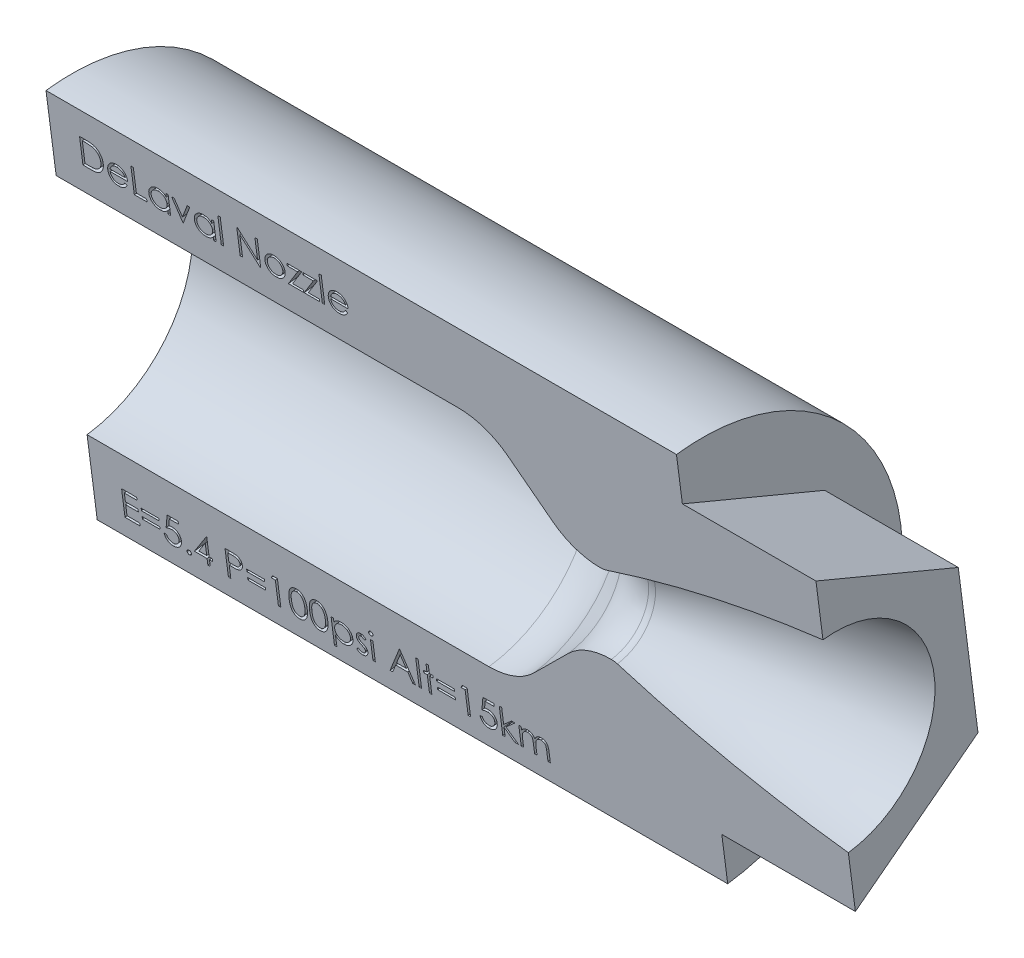
SolidWorks part; units mm, degrees
ref_plane "Front Plane" through (0, 0, 0) normal (0, 0, 1) x (1, 0, 0)
ref_plane "Top Plane" through (0, 0, 0) normal (0, 1, 0) x (1, 0, 0)
ref_plane "Right Plane" through (0, 0, 0) normal (1, 0, 0) x (0, 0, -1)
sketch "Sketch1" plane through (0, 0, 0) normal (0, 0, 1) x (1, 0, 0)
  line L0 (0, 0) -> (10.9228, 0) construction
  line L1 (0.278, 2.081) -> (10.9228, 5.9554) construction
  line L2 (-2.1553, 2.9247) -> (-4.048, 4.8174)
  line L3 (-25.4, 5.7474) -> (-25.4, 9.525)
  line L4 (-6.293, 5.7474) -> (-25.4, 5.7474)
  line L5 (-25.4, 9.525) -> (-1.7772, 9.525)
  line L6 (10.9228, 9.525) -> (10.9228, 4.7219)
  line L7 (10.9228, 4.7219) -> (12.711, 4.9733) construction
  line L8 (-1.7772, 9.525) -> (10.9228, 9.525)
  arc A0 (-2.1553, 2.9247) -> (0, 2.032) centre (0, 5.08) ccw
  arc A1 (0, 2.032) -> (0.278, 2.081) centre (0, 2.8448) ccw
  arc A2 (-4.048, 4.8174) -> (-6.293, 5.7474) centre (-6.293, 2.5724) ccw
  parabola Q0 (10.9228, 4.7219) -> (0.278, 2.081) focus (9.0524, -22.0264) apex (0.278, 2.081)
  dimension "D3" = 3.048
  dimension "D4" = 0.8128
  dimension "D11" = 3.175
  dimension "D12" = 8
  dimension "D1" = 2.032
  dimension "D2" = 10.9228
  dimension "D5" = 4.7219
  dimension "D6" = 20
  dimension "D7" = 45
  dimension "D8" = 5.7474
  dimension "D9" = 25.4
  dimension "D10" = 9.525
  dimension "D13" = 12.7
revolve "Revolve1" add sketch "Sketch1" angle 360 about L0
sketch "Sketch3" plane through (10.9228, 0, 0) normal (1, 0, 0) x (0, 0, -1)
  line L1 (0.9374, -7.2722) -> (6.7666, -2.8242)
  line L2 (6.7666, -2.8242) -> (5.8292, 4.4479)
  line L3 (5.8292, 4.4479) -> (-0.9374, 7.2722)
  line L4 (-0.9374, 7.2722) -> (-6.7666, 2.8242)
  line L5 (-6.7666, 2.8242) -> (-5.8292, -4.4479)
  line L6 (-5.8292, -4.4479) -> (0.9374, -7.2722)
  circle A0 centre (0, 0) radius 6.35 construction
  circle M7 centre (0, 0) radius 9.525
  dimension "D1" = 12.7
extrude "Cut-Extrude2" cut sketch "Sketch3" against normal blind 6.35 contours L6 L5 L4 L3 L2 L1 M7
sketch "Sketch4" plane through (10.9228, 0, 0) normal (1, 0, 0) x (0, 0, -1)
  line L0 (1.606, -12.4589) -> (-1.4282, 11.0794)
  line L1 (-1.4282, 11.0794) -> (-11.4972, 10.005)
  line L2 (-11.4972, 10.005) -> (-9.1004, -12.4589)
  line L3 (-9.1004, -12.4589) -> (1.606, -12.4589)
extrude "Cut-Extrude3" cut sketch "Sketch4" against normal through all
sketch "Sketch5" plane through (0, 0, 0) normal (0, -0.1278, 0.9918) x (1, 0, 0)
  line L0 (-25.4, 5.7474) -> (-25.4, 9.525) construction
  text T0 "DeLaval Nozzle" font "Century Gothic" height 1.27
  text T1 "E=5.4 P=100psi Alt=15km" font "Century Gothic" height 1.27
  dimension "D1" = 1.27
extrude "Cut-Extrude4" cut sketch "Sketch5" against normal blind 0.635
equation "\"D3@Sketch1\"= 1.5 * \"D1@Sketch1\""
equation "\"D4@Sketch1\"=.4 * \"D1@Sketch1\""
equation "\"D5@Sketch1\"=\"D1@Sketch1\" * ( 5.4 ) ^ .5"
equation "\"D8@Sketch1\"=\"D1@Sketch1\" * ( 8 ) ^ .5"
equation "\"er\"= 4"
